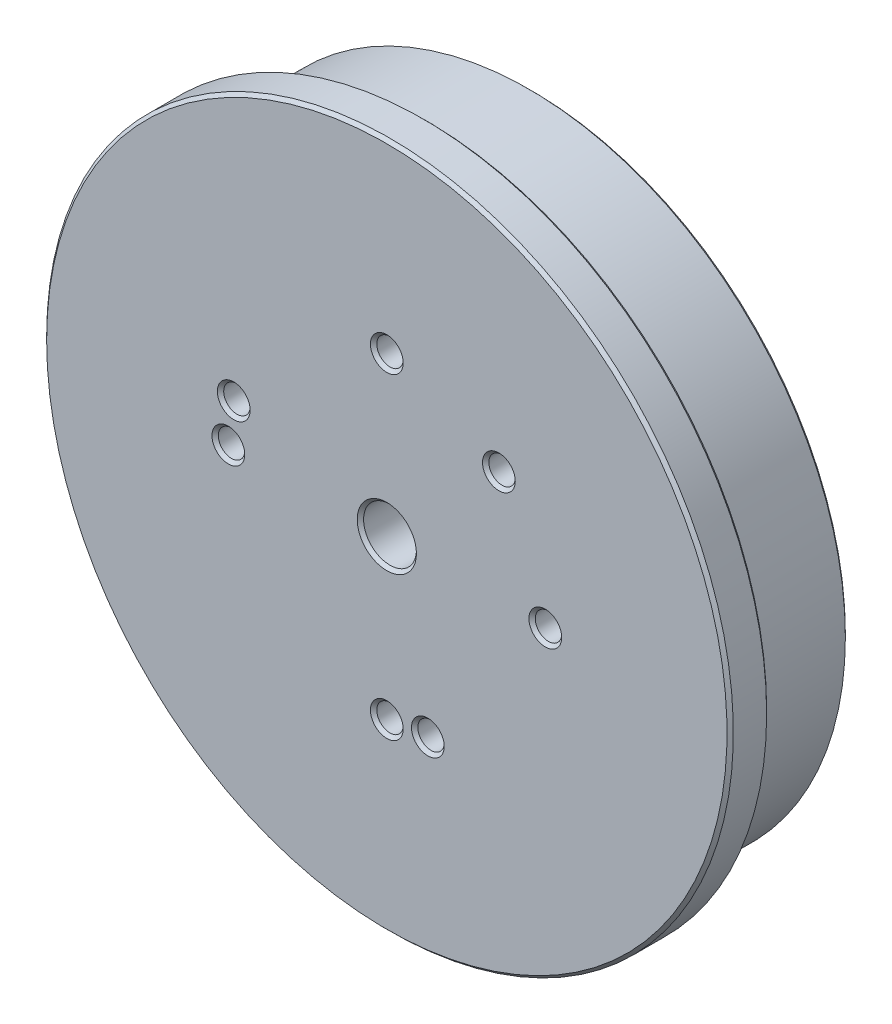
SolidWorks part; units mm, degrees
ref_plane "Front Plane" through (0, 0, 0) normal (0, 0, 1) x (1, 0, 0)
ref_plane "Top Plane" through (0, 0, 0) normal (0, 1, 0) x (1, 0, 0)
ref_plane "Right Plane" through (0, 0, 0) normal (1, 0, 0) x (0, 0, -1)
sketch "Sketch1" plane through (0, 0, 0) normal (0, 0, 1) x (1, 0, 0)
  circle A0 centre (0, 0) radius 76.073
  dimension "D1" = 152.146
extrude "Boss-Extrude1" add sketch "Sketch1" along normal blind 25.4
sketch "Sketch2" plane through (0, 0, 25.4) normal (0, 0, 1) x (1, 0, 0)
  circle A0 centre (0, 0) radius 82.55
  dimension "D1" = 165.1
extrude "Boss-Extrude2" add sketch "Sketch2" along normal blind 9.525
sketch "Sketch3" plane through (0, 0, 34.925) normal (0, 0, 1) x (1, 0, 0)
  line L0 (0, 0) -> (0, 38.1) construction
  line L1 (0, 0) -> (38.1, 0) construction
  line L2 (0, 0) -> (0, -38.1) construction
  line L3 (0, 0) -> (-38.1, 0) construction
  line L4 (0, 0) -> (26.9408, 26.9408) construction
  line L5 (0, 0) -> (9.861, -36.8018) construction
  line L6 (0, 0) -> (-36.8018, 9.861) construction
  circle A0 centre (0, 38.1) radius 3.175
  circle A1 centre (26.9408, 26.9408) radius 3.175
  circle A2 centre (38.1, 0) radius 3.175
  circle A3 centre (9.861, -36.8018) radius 3.175
  circle A4 centre (0, -38.1) radius 3.175
  circle A5 centre (-38.1, 0) radius 3.175
  circle A6 centre (-36.8018, 9.861) radius 3.175
  dimension "D4" = 6.35
  dimension "D1" = 45
  dimension "D2" = 120
  dimension "D3" = 120
  dimension "D5" = 38.1
extrude "Cut-Extrude1" cut sketch "Sketch3" against normal through all
sketch "Sketch5" plane through (0, 0, 34.925) normal (0, 0, 1) x (1, 0, 0)
  circle A0 centre (0, 0) radius 6.35
  dimension "D1" = 12.7
extrude "Cut-Extrude2" cut sketch "Sketch5" against normal through all
chamfer "Chamfer1" distance 0.762 angle 45 19 edges at (76.073, 0, 0) (30.1158, 26.9408, 0) (41.275, 0, 0) (3.175, 38.1, 0) (13.036, -36.8018, 0) (3.175, -38.1, 0) (-34.925, 0, 0) (-33.6268, 9.861, 0) (6.35, 0, 0) (82.55, 0, 34.925) (30.1158, 26.9408, 34.925) (41.275, 0, 34.925) (3.175, 38.1, 34.925) (13.036, -36.8018, 34.925) (3.175, -38.1, 34.925) (-34.925, 0, 34.925) (-33.6268, 9.861, 34.925) (6.35, 0, 34.925) (82.55, 0, 25.4)
